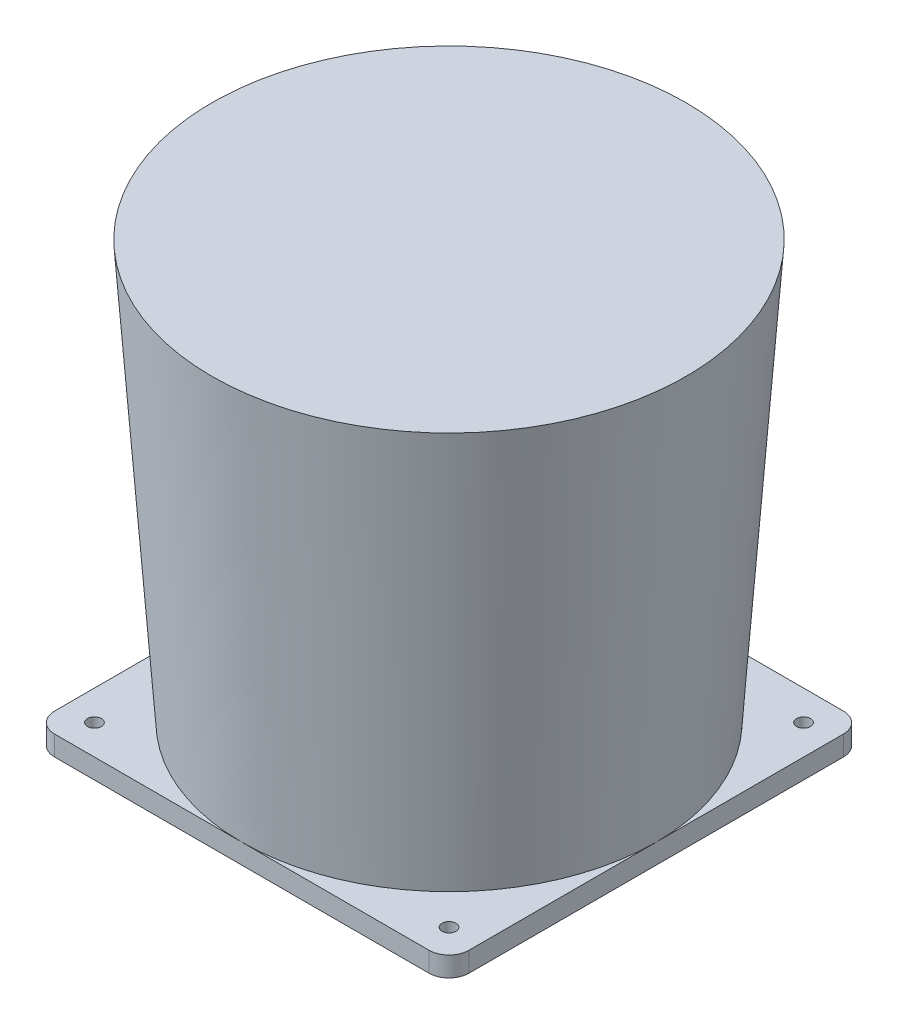
SolidWorks part; units mm, degrees
ref_plane "Front Plane" through (0, 0, 0) normal (0, 0, 1) x (1, 0, 0)
ref_plane "Top Plane" through (0, 0, 0) normal (0, 1, 0) x (1, 0, 0)
ref_plane "Right Plane" through (0, 0, 0) normal (1, 0, 0) x (0, 0, -1)
sketch "Sketch5" plane through (0, 0, 0) normal (0, 1, 0) x (1, 0, 0)
  line L0 (-94, 104) -> (94, 104)
  line L1 (-89, 89) -> (89, 89) construction
  line L2 (-89, 89) -> (-89, -89) construction
  line L3 (-89, -89) -> (89, -89) construction
  line L4 (89, 89) -> (89, -89) construction
  line L5 (-89, 89) -> (89, -89) construction
  line L6 (-89, -89) -> (89, 89) construction
  line L7 (104, 94) -> (104, -94)
  line L8 (-94, -104) -> (94, -104)
  line L9 (-104, 94) -> (-104, -94)
  line L10 (-104, 104) -> (104, 104) construction
  line L11 (104, 104) -> (104, -104) construction
  line L12 (-104, -104) -> (104, -104) construction
  line L13 (-104, 104) -> (-104, -104) construction
  circle A0 centre (-89, 89) radius 3.5
  circle A1 centre (89, 89) radius 3.5
  circle A2 centre (89, -89) radius 3.5
  circle A3 centre (-89, -89) radius 3.5
  arc A4 (94, 104) -> (104, 94) centre (94, 94) cw
  arc A5 (104, -94) -> (94, -104) centre (94, -94) cw
  arc A6 (-94, -104) -> (-104, -94) centre (-94, -94) cw
  arc A7 (-104, 94) -> (-94, 104) centre (-94, 94) cw
  point P0 (0, 0)
  dimension "D4" = 7
  dimension "D7" = 10
  dimension "D1" = 178
  dimension "D2" = 178
  dimension "D3" = 15
  dimension "D5" = 2
  dimension "D6" = 2
extrude "Boss-Extrude2" add sketch "Sketch5" along normal blind 10
sketch "Sketch6" plane through (0, 10, 0) normal (0, 1, 0) x (1, 0, 0)
  circle A0 centre (0, 0) radius 104
  dimension "D1" = 208
ref_plane "Plane2" through (0, 220, 0) normal (0, 1, 0) x (1, 0, 0)
sketch "Sketch7" plane through (0, 220, 0) normal (0, 1, 0) x (1, 0, 0)
  circle A0 centre (0, 0) radius 119
  dimension "D1" = 238
loft "Loft3" add profiles "Sketch7", "Sketch6"
